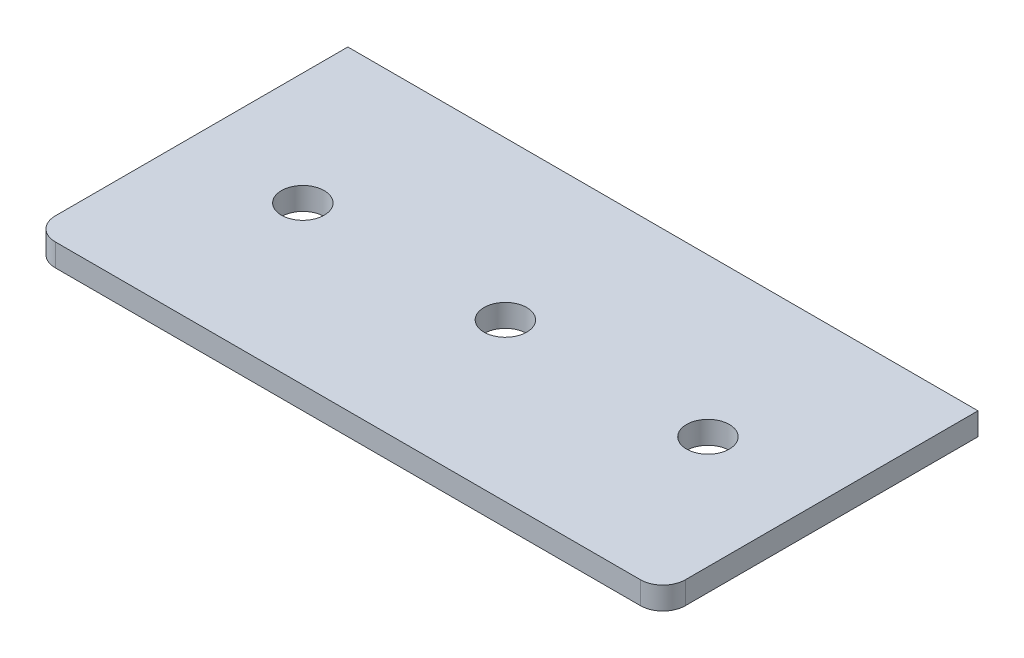
SolidWorks part; units mm, degrees
material "Plain Carbon Steel"
ref_plane "Front Plane" through (0, 0, 0) normal (0, 0, 1) x (1, 0, 0)
ref_plane "Top Plane" through (0, 0, 0) normal (0, 1, 0) x (1, 0, 0)
ref_plane "Right Plane" through (0, 0, 0) normal (1, 0, 0) x (0, 0, -1)
sketch "Sketch1" plane through (0, 0, 0) normal (0, 1, 0) x (1, 0, 0)
  line L1 (-140, -70) -> (140, -70)
  line L2 (-140, -70) -> (-140, 70)
  line L3 (-140, 70) -> (140, 70)
  line L4 (140, -70) -> (140, 70)
  line L5 (-140, -70) -> (140, 70) construction
  line L6 (-140, 70) -> (140, -70) construction
  point P0 (0, 0)
  dimension "D1" = 280
  dimension "D2" = 140
extrude "Boss-Extrude1" add sketch "Sketch1" along normal blind 10
sketch "Sketch2" plane through (0, 10, 0) normal (0, 1, 0) x (1, 0, 0)
  line L0 (-140, 70) -> (-140, -70) construction
  line L2 (140, 70) -> (-140, 70) construction
  circle A0 centre (-90, 0) radius 9.5
  circle A1 centre (0, 0) radius 9.5
  dimension "D2" = 70
  dimension "D3" = 19
  dimension "D1" = 50
extrude "Cut-Extrude1" cut sketch "Sketch2" against normal blind 10
mirror "Mirror1" about plane through (0, 0, 0) normal (1, 0, 0) of "Cut-Extrude1"
fillet "Fillet1" radius 10 2 edges at (140, 5, 70) (-140, 5, 70)
